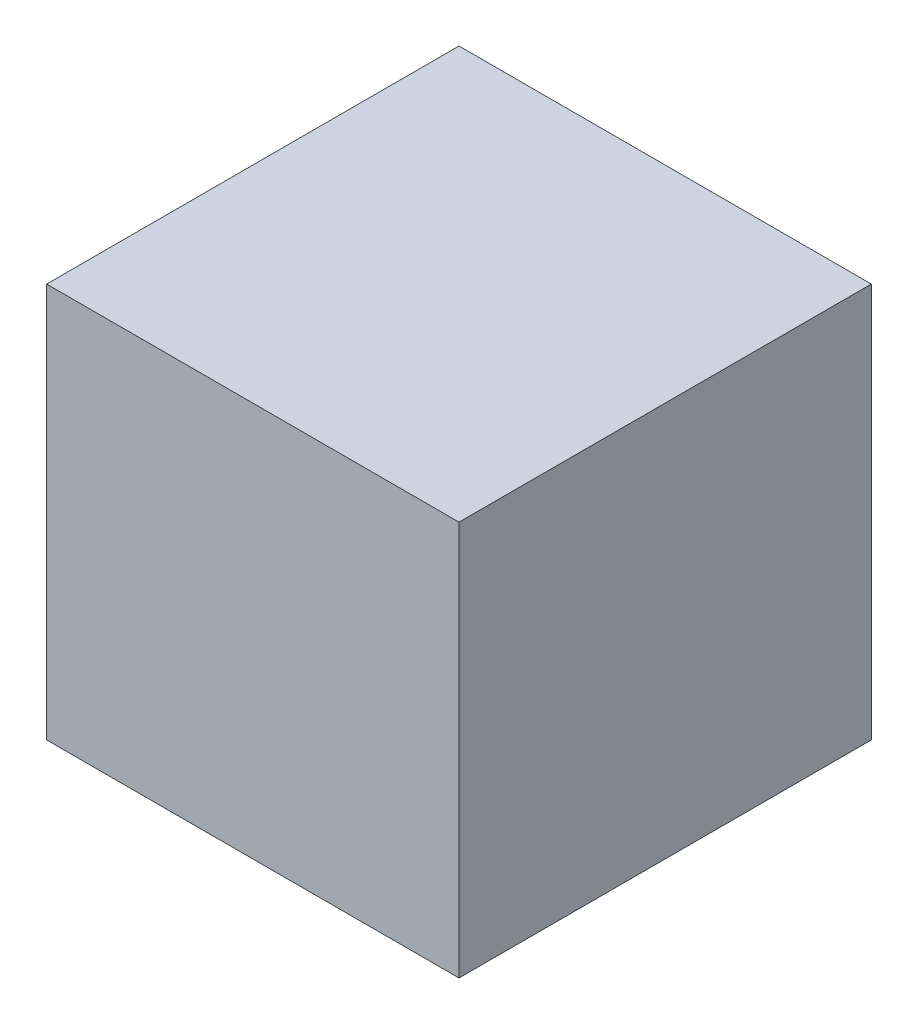
SolidWorks part; units mm, degrees
ref_plane "前视基准面" through (0, 0, 0) normal (0, 0, 1) x (1, 0, 0)
ref_plane "上视基准面" through (0, 0, 0) normal (0, 1, 0) x (1, 0, 0)
ref_plane "右视基准面" through (0, 0, 0) normal (1, 0, 0) x (0, 0, -1)
sketch "草图1" plane through (0, 0, 0) normal (0, 1, 0) x (1, 0, 0)
  line L1 (-47, 47) -> (47, 47)
  line L2 (-47, 47) -> (-47, -47)
  line L3 (-47, -47) -> (47, -47)
  line L4 (47, 47) -> (47, -47)
  line L5 (-47, 47) -> (47, -47) construction
  line L6 (-47, -47) -> (47, 47) construction
  point P0 (0, 0)
  dimension "D1" = 94
  dimension "D2" = 94
extrude "凸台-拉伸1" add sketch "草图1" along normal blind 90
